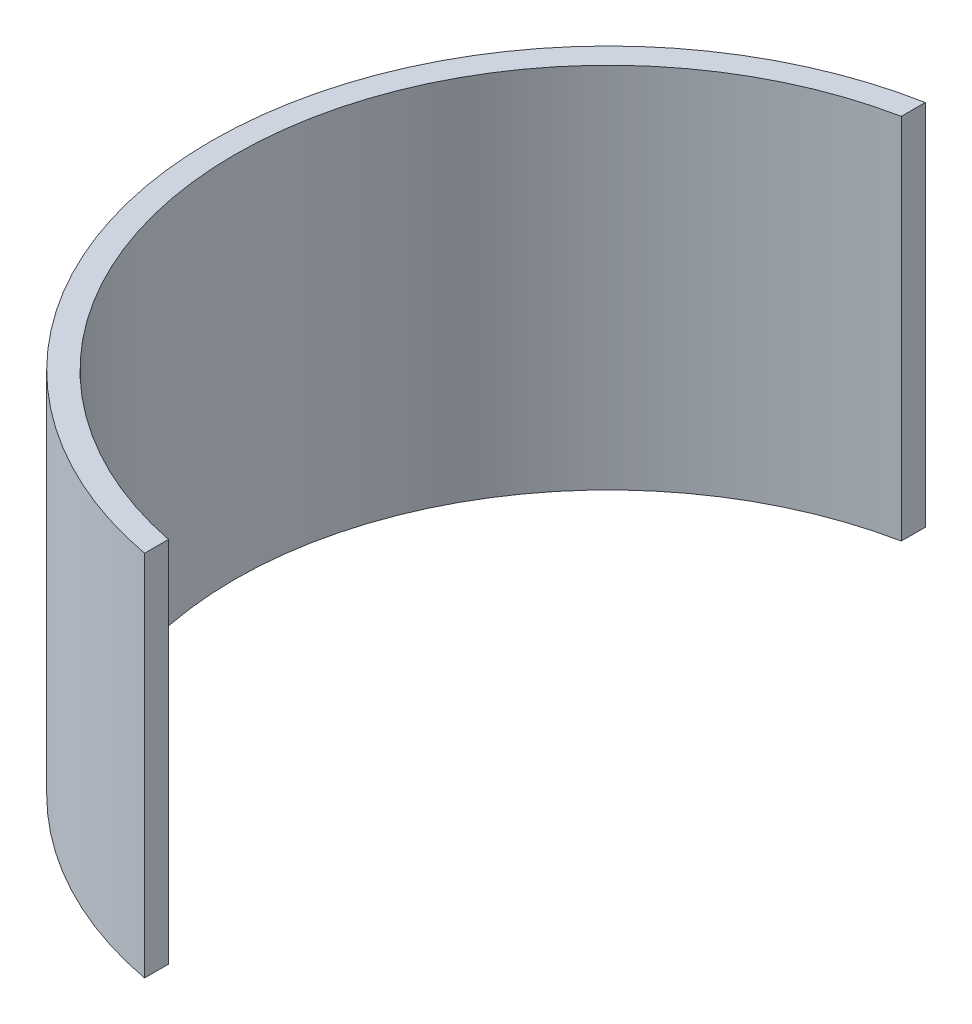
SolidWorks part; units mm, degrees
material "BUTYL"
ref_plane "Front Plane" through (0, 0, 0) normal (0, 0, 1) x (1, 0, 0)
ref_plane "Top Plane" through (0, 0, 0) normal (0, 1, 0) x (1, 0, 0)
ref_plane "Right Plane" through (0, 0, 0) normal (1, 0, 0) x (0, 0, -1)
sketch "Sketch1" plane through (0, 0, 0) normal (0, 1, 0) x (1, 0, 0)
  line L0 (0, 54) -> (0, 50.8)
  line L1 (0, -50.8) -> (0, -54)
  arc A0 (0, 54) -> (0, -54) centre (0, 0) ccw
  arc A1 (0, 50.8) -> (0, -50.8) centre (0, 0) ccw
  dimension "D1" = 108
  dimension "D2" = 101.6
extrude "Boss-Extrude1" add sketch "Sketch1" along normal blind 50
sketch "Sketch2" plane through (0, 50, 0) normal (0, 1, 0) x (1, 0, 0)
  line L1 (0, -54) -> (-10, -54)
  line L2 (0, -54) -> (0, 54)
  line L3 (0, 54) -> (-10, 54)
  line L4 (-10, -54) -> (-10, 54)
  dimension "D1" = 10
  dimension "D2" = 108
extrude "Cut-Extrude1" cut sketch "Sketch2" against normal through all
